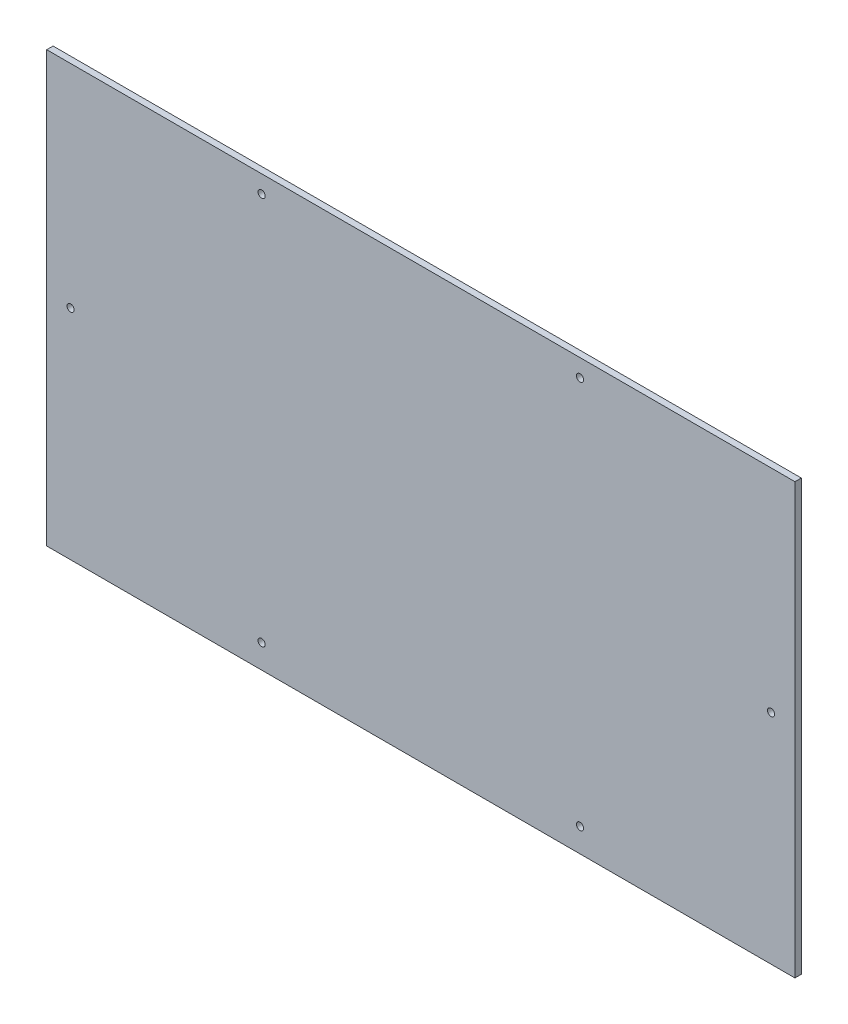
SolidWorks part; units mm, degrees
material "PC"
ref_plane "Front Plane" through (0, 0, 0) normal (0, 0, 1) x (1, 0, 0)
ref_plane "Top Plane" through (0, 0, 0) normal (0, 1, 0) x (1, 0, 0)
ref_plane "Right Plane" through (0, 0, 0) normal (1, 0, 0) x (0, 0, -1)
sketch "Sketch1" plane through (0, 0, 0) normal (0, 0, 1) x (1, 0, 0)
  line L1 (-235, 0) -> (235, 0)
  line L2 (-235, 0) -> (-235, -270)
  line L3 (-235, -270) -> (235, -270)
  line L4 (235, 0) -> (235, -270)
  dimension "D1" = 470
  dimension "D2" = 270
extrude "Boss-Extrude1" add sketch "Sketch1" along normal mid plane 4
sketch "Sketch2" plane through (0, 0, 2) normal (0, 0, 1) x (1, 0, 0)
  line L0 (-100, -255) -> (-100, -11) construction
  line L1 (-220, -133) -> (-100, -133) construction
  line L2 (-235, 0) -> (-235, -270) construction
  line L3 (235, 0) -> (-235, 0) construction
  line L4 (-235, -270) -> (235, -270) construction
  line L5 (0, -22.7225) -> (0, -81.7266) construction
  line L6 (235, -270) -> (235, 0) construction
  circle A0 centre (-220, -133) radius 2.25
  circle A1 centre (-100, -11) radius 2.25
  circle A2 centre (-100, -255) radius 2.25
  circle A3 centre (220, -133) radius 2.25
  circle A4 centre (100, -255) radius 2.25
  circle A5 centre (100, -11) radius 2.25
  dimension "D1" = 4.5
  dimension "D3" = 11
  dimension "D2" = 15
  dimension "D4" = 15
  dimension "D5" = 15
  dimension "D6" = 200
extrude "Cut-Extrude1" cut sketch "Sketch2" against normal through all
